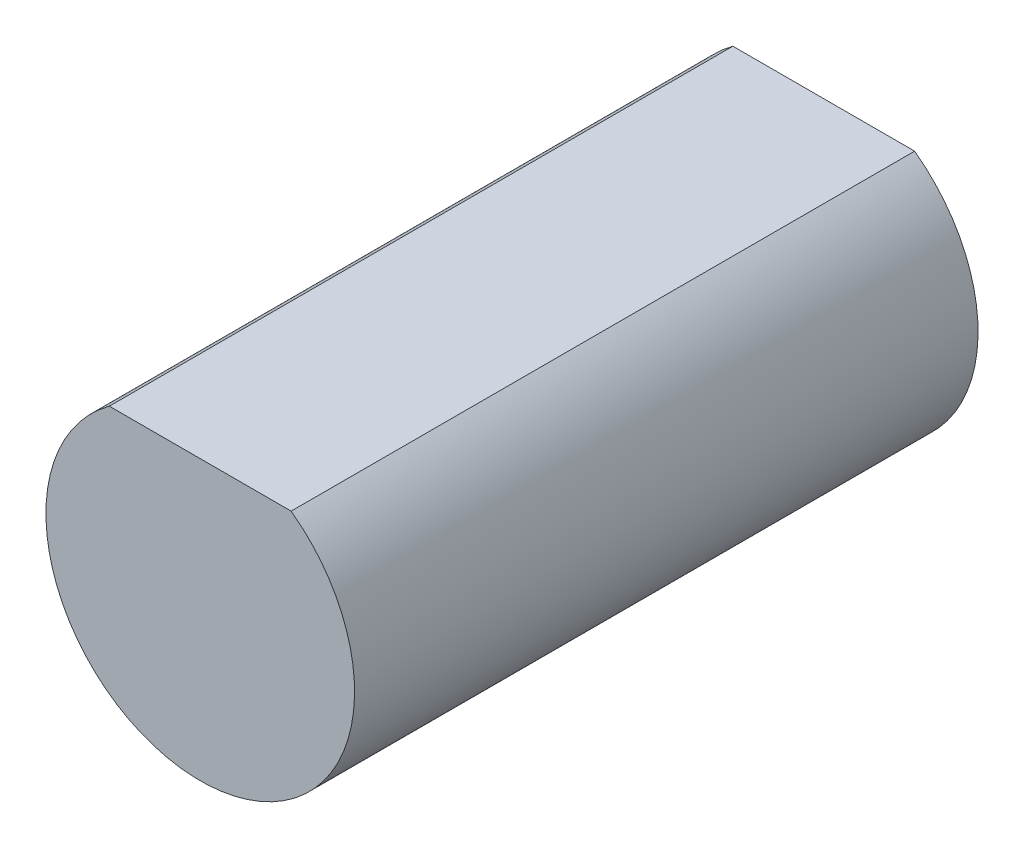
SolidWorks part; units mm, degrees
ref_plane "前视基准面" through (0, 0, 0) normal (0, 0, 1) x (1, 0, 0)
ref_plane "上视基准面" through (0, 0, 0) normal (0, 1, 0) x (1, 0, 0)
ref_plane "右视基准面" through (0, 0, 0) normal (1, 0, 0) x (0, 0, -1)
other "Configuration Table"
sketch "草图1" plane through (0, 0, 0) normal (0, 0, 1) x (1, 0, 0)
  circle A0 centre (0, 0) radius 9.9
  dimension "D1" = 19.8
extrude "凸台-拉伸1" add sketch "草图1" along normal blind 40
sketch "草图2" plane through (0, 0, 40) normal (0, 0, 1) x (1, 0, 0)
  line L0 (-6, 8) -> (6, 8)
  arc A0 (6, 8) -> (-6, 8) centre (0, 0) ccw
  dimension "D1" = 20
  dimension "D2" = 8
extrude "切除-拉伸1" cut sketch "草图2" against normal through all
